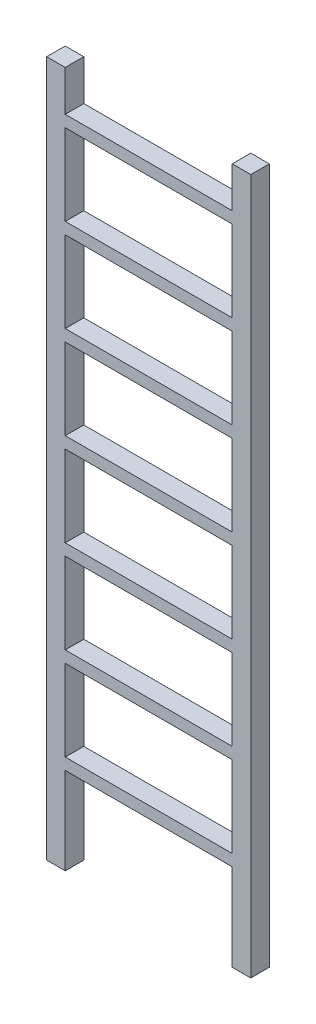
SolidWorks part; units mm, degrees
ref_plane "前视基准面" through (0, 0, 0) normal (0, 0, 1) x (1, 0, 0)
ref_plane "上视基准面" through (0, 0, 0) normal (0, 1, 0) x (1, 0, 0)
ref_plane "右视基准面" through (0, 0, 0) normal (1, 0, 0) x (0, 0, -1)
other "Configuration Table"
sketch "草图1" plane through (0, 0, 0) normal (0, 0, 1) x (1, 0, 0)
  line L1 (-440, -1500) -> (-360, -1500)
  line L2 (-440, -1500) -> (-440, 1500)
  line L3 (-440, 1500) -> (-360, 1500)
  line L4 (-360, -1500) -> (-360, 1500)
  line L5 (-440, -1500) -> (-360, 1500) construction
  line L6 (-440, 1500) -> (-360, -1500) construction
  point P0 (-400, 0)
extrude "凸台-拉伸1" add sketch "草图1" along normal blind 80
sketch "草图2" plane through (0, 0, 0) normal (0, 0, 1) x (1, 0, 0)
  line L1 (360, -1500) -> (440, -1500)
  line L2 (360, -1500) -> (360, 1500)
  line L3 (360, 1500) -> (440, 1500)
  line L4 (440, -1500) -> (440, 1500)
  line L5 (360, -1500) -> (440, 1500) construction
  line L6 (360, 1500) -> (440, -1500) construction
  point P0 (400, 0)
extrude "凸台-拉伸2" add sketch "草图2" along normal blind 80
sketch "草图3" plane through (0, 0, 0) normal (0, 0, 1) x (1, 0, 0)
  line L1 (-400, 1275) -> (400, 1275)
  line L2 (-400, 1275) -> (-400, 1325)
  line L3 (-400, 1325) -> (400, 1325)
  line L4 (400, 1275) -> (400, 1325)
  line L5 (-400, 1275) -> (400, 1325) construction
  line L6 (-400, 1325) -> (400, 1275) construction
  point P0 (0, 1300)
extrude "凸台-拉伸3" add sketch "草图3" along normal blind 80
sketch "草图4" plane through (0, 0, 0) normal (0, 0, 1) x (1, 0, 0)
  line L1 (-400, 875) -> (400, 875)
  line L2 (-400, 875) -> (-400, 925)
  line L3 (-400, 925) -> (400, 925)
  line L4 (400, 875) -> (400, 925)
  line L5 (-400, 875) -> (400, 925) construction
  line L6 (-400, 925) -> (400, 875) construction
  point P0 (0, 900)
extrude "凸台-拉伸4" add sketch "草图4" along normal blind 80
sketch "草图5" plane through (0, 0, 0) normal (0, 0, 1) x (1, 0, 0)
  line L1 (-400, 475) -> (400, 475)
  line L2 (-400, 475) -> (-400, 525)
  line L3 (-400, 525) -> (400, 525)
  line L4 (400, 475) -> (400, 525)
  line L5 (-400, 475) -> (400, 525) construction
  line L6 (-400, 525) -> (400, 475) construction
  point P0 (0, 500)
extrude "凸台-拉伸5" add sketch "草图5" along normal blind 80
sketch "草图6" plane through (0, 0, 0) normal (0, 0, 1) x (1, 0, 0)
  line L1 (-400, 75) -> (400, 75)
  line L2 (-400, 75) -> (-400, 125)
  line L3 (-400, 125) -> (400, 125)
  line L4 (400, 75) -> (400, 125)
  line L5 (-400, 75) -> (400, 125) construction
  line L6 (-400, 125) -> (400, 75) construction
  point P0 (0, 100)
extrude "凸台-拉伸6" add sketch "草图6" along normal blind 80
sketch "草图7" plane through (0, 0, 0) normal (0, 0, 1) x (1, 0, 0)
  line L1 (-400, -325) -> (400, -325)
  line L2 (-400, -325) -> (-400, -275)
  line L3 (-400, -275) -> (400, -275)
  line L4 (400, -325) -> (400, -275)
  line L5 (-400, -325) -> (400, -275) construction
  line L6 (-400, -275) -> (400, -325) construction
  point P0 (0, -300)
extrude "凸台-拉伸7" add sketch "草图7" along normal blind 80
sketch "草图8" plane through (0, 0, 0) normal (0, 0, 1) x (1, 0, 0)
  line L1 (-400, -725) -> (400, -725)
  line L2 (-400, -725) -> (-400, -675)
  line L3 (-400, -675) -> (400, -675)
  line L4 (400, -725) -> (400, -675)
  line L5 (-400, -725) -> (400, -675) construction
  line L6 (-400, -675) -> (400, -725) construction
  point P0 (0, -700)
extrude "凸台-拉伸8" add sketch "草图8" along normal blind 80
sketch "草图9" plane through (0, 0, 0) normal (0, 0, 1) x (1, 0, 0)
  line L1 (-400, -1125) -> (400, -1125)
  line L2 (-400, -1125) -> (-400, -1075)
  line L3 (-400, -1075) -> (400, -1075)
  line L4 (400, -1125) -> (400, -1075)
  line L5 (-400, -1125) -> (400, -1075) construction
  line L6 (-400, -1075) -> (400, -1125) construction
  point P0 (0, -1100)
extrude "凸台-拉伸9" add sketch "草图9" along normal blind 80
